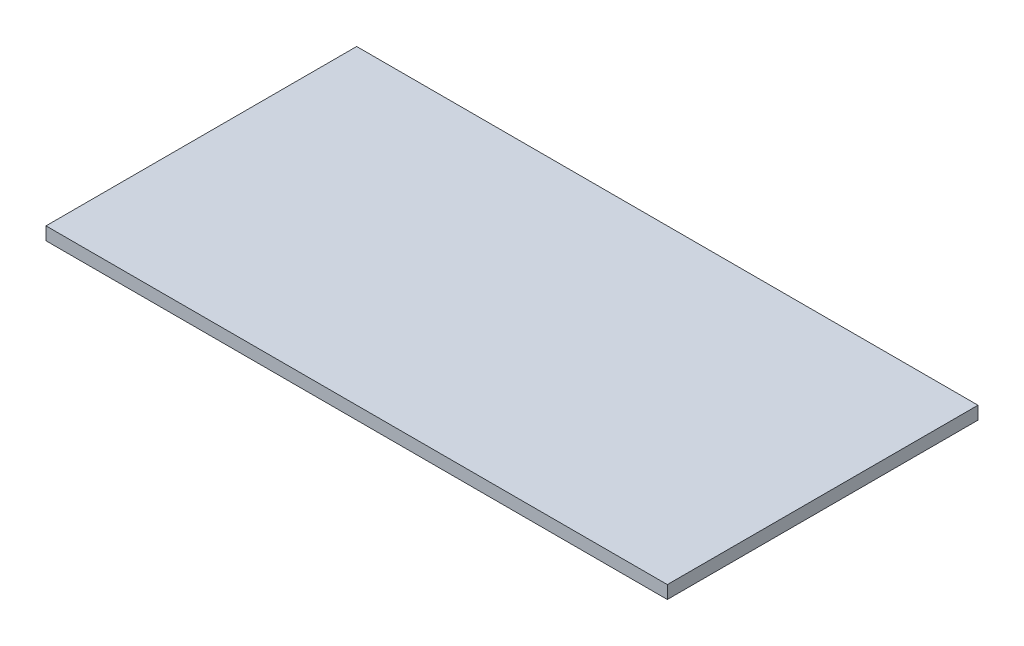
SolidWorks part; units mm, degrees
ref_plane "Front Plane" through (0, 0, 0) normal (0, 0, 1) x (1, 0, 0)
ref_plane "Top Plane" through (0, 0, 0) normal (0, 1, 0) x (1, 0, 0)
ref_plane "Right Plane" through (0, 0, 0) normal (1, 0, 0) x (0, 0, -1)
sketch "Sketch1" plane through (0, 0, 0) normal (0, 1, 0) x (1, 0, 0)
  line L1 (152.4, 76.2) -> (-152.4, 76.2)
  line L2 (152.4, 76.2) -> (152.4, -76.2)
  line L3 (152.4, -76.2) -> (-152.4, -76.2)
  line L4 (-152.4, 76.2) -> (-152.4, -76.2)
  line L5 (152.4, 76.2) -> (-152.4, -76.2) construction
  line L6 (152.4, -76.2) -> (-152.4, 76.2) construction
  point P0 (0, 0)
  dimension "D1" = 152.4
  dimension "D2" = 304.8
extrude "Boss-Extrude1" add sketch "Sketch1" along normal blind 6.35
sketch "Sketch2" plane through (0, 6.35, 0) normal (0, 1, 0) x (1, 0, 0)
  line L0 (-83.7348, 9.4705) -> (-53.878, 19.8354)
  line L1 (-53.878, 19.8354) -> (-30.5512, 19.8354)
  line L2 (-30.5512, 19.8354) -> (-9.9656, 9.4705)
  line L3 (-9.9656, 9.4705) -> (34.3834, 3.3756)
  line L4 (34.3834, 3.3756) -> (36.6526, -3.1609)
  line L5 (36.6526, -3.1609) -> (34.1218, -8.1872)
  line L6 (34.1218, -8.1872) -> (9.1714, -8.1872)
  line L7 (9.1714, -8.1872) -> (-60.7194, -8.1872)
  line L8 (-60.7194, -8.1872) -> (-83.7348, -0.2676)
  line L9 (-83.7348, -0.2676) -> (-83.7348, 9.4705)
  line L10 (-80.0911, 9.0807) -> (-58.9656, 16.1225)
  line L11 (-58.9656, 16.1225) -> (-58.9656, 9.0807)
  line L12 (-58.9656, 9.0807) -> (-80.0911, 9.0807)
  line L13 (-53.878, 16.1225) -> (-53.878, 9.4705)
  line L14 (-53.878, 9.4705) -> (-52.2601, 9.4705)
  line L15 (-16.6887, 9.4705) -> (-30.5512, 17.7601)
  line L16 (-30.5512, 17.7601) -> (-53.878, 17.7601)
  line L17 (-53.878, 17.7601) -> (-53.878, 16.1225)
  line L18 (-47.1384, 9.4705) -> (-43.691, 13.0746)
  line L19 (-43.691, 13.0746) -> (-34.8616, 13.0746)
  line L20 (-34.8616, 13.0746) -> (-26.4058, 9.4705)
  line L22 (-52.2601, 9.4705) -> (-49.2687, 9.4705)
  line L23 (-52.2601, 9.4705) -> (-52.2601, 15.1089)
  line L24 (-52.2601, 15.1089) -> (-49.2687, 15.1089)
  line L25 (-49.2687, 9.4705) -> (-49.2687, 15.1089)
  line L26 (-49.2687, 9.4705) -> (-16.6887, 9.4705)
  circle A0 centre (-60.7194, -8.1872) radius 8.9225
  circle A1 centre (9.1714, -8.1872) radius 8.9566
